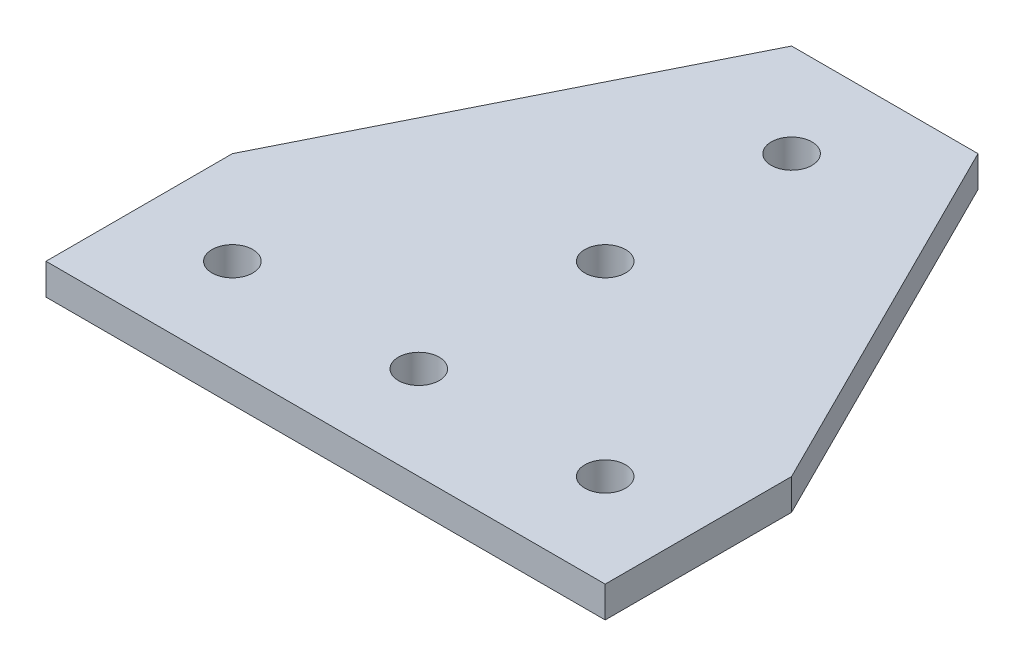
SolidWorks part; units mm, degrees
material "6105-T5 Aluminum"
ref_plane "Front Plane" through (0, 0, 0) normal (0, 0, 1) x (1, 0, 0)
ref_plane "Top Plane" through (0, 0, 0) normal (0, 1, 0) x (1, 0, 0)
ref_plane "Right Plane" through (0, 0, 0) normal (1, 0, 0) x (0, 0, -1)
sketch "Sketch1" plane through (0, 0, 0) normal (0, 0, 1) x (1, 0, 0)
  line L1 (-57.15, -3.175) -> (57.15, -3.175)
  line L2 (-57.15, -3.175) -> (-57.15, 3.175)
  line L3 (-57.15, 3.175) -> (57.15, 3.175)
  line L4 (57.15, -3.175) -> (57.15, 3.175)
  line L5 (-57.15, -3.175) -> (57.15, 3.175) construction
  line L6 (-57.15, 3.175) -> (57.15, -3.175) construction
  point P0 (0, 0)
  dimension "D1" = 114.3
  dimension "D2" = 6.35
extrude "Boss-Extrude1" add sketch "Sketch1" along normal mid plane 114.3
sketch "Sketch2" plane through (0, 3.175, 0) normal (0, 1, 0) x (1, 0, 0)
  line L0 (-57.15, -19.05) -> (-19.05, 57.15)
  line L1 (-57.15, -57.15) -> (-57.15, 57.15) construction
  line L2 (57.15, 57.15) -> (-57.15, 57.15) construction
  line L3 (-19.05, 57.15) -> (-57.15, 57.15)
  line L4 (-57.15, 57.15) -> (-57.15, -19.05)
  line L5 (57.15, -19.05) -> (19.05, 57.15)
  line L6 (57.15, -57.15) -> (57.15, 57.15) construction
  line L7 (19.05, 57.15) -> (57.15, 57.15)
  line L8 (57.15, 57.15) -> (57.15, -19.05)
  line L9 (57.15, -57.15) -> (-57.15, -57.15) construction
  dimension "D1" = 38.1
  dimension "D2" = 38.1
  dimension "D3" = 76.2
extrude "Cut-Extrude1" cut sketch "Sketch2" against normal through all
sketch "Sketch3" plane through (0, 3.175, 0) normal (0, 1, 0) x (1, 0, 0)
  line L0 (0, 57.15) -> (0, -57.15) construction
  line L1 (19.05, 57.15) -> (-19.05, 57.15) construction
  line L2 (57.15, -57.15) -> (-57.15, -57.15) construction
  circle A0 centre (0, 38.1) radius 4.1656
  dimension "D1" = 8.3312
  dimension "D2" = 38.1
extrude "Cut-Extrude2" cut sketch "Sketch3" against normal through all
pattern_linear "LPattern1" count 3 spacing 38.1 along (0, 0, 1) of "Cut-Extrude2"
sketch "Sketch4" plane through (0, 3.175, 0) normal (0, 1, 0) x (1, 0, 0)
  line L0 (0, 24.0617) -> (0, 11.4517) construction
  circle A0 centre (-38.1, -38.1) radius 4.1656
  circle A1 centre (38.1, -38.1) radius 4.1656
  dimension "D1" = 8.3312
  dimension "D2" = 38.1
  dimension "D3" = 38.1
extrude "Cut-Extrude3" cut sketch "Sketch4" against normal through all
